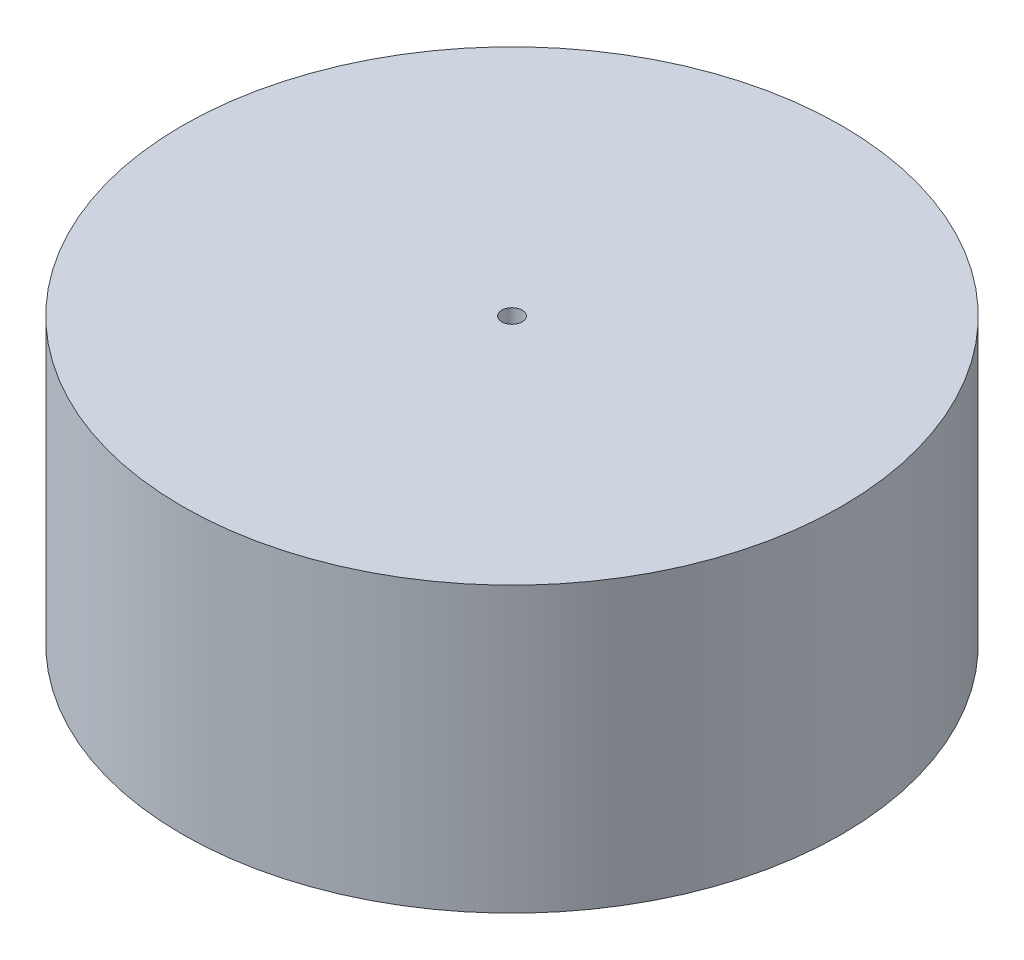
SolidWorks part; units mm, degrees
ref_plane "Front Plane" through (0, 0, 0) normal (0, 0, 1) x (1, 0, 0)
ref_plane "Top Plane" through (0, 0, 0) normal (0, 1, 0) x (1, 0, 0)
ref_plane "Right Plane" through (0, 0, 0) normal (1, 0, 0) x (0, 0, -1)
sketch "Sketch1" plane through (0, 0, 0) normal (0, 1, 0) x (1, 0, 0)
  circle A0 centre (0, 0) radius 32.5
  circle A1 centre (0, 0) radius 1
  dimension "D1" = 65
  dimension "D2" = 2
extrude "Boss-Extrude1" add sketch "Sketch1" along normal blind 3
sketch "Sketch3" plane through (0, 0, 0) normal (0, -1, 0) x (1, 0, 0)
  circle A0 centre (0, 0) radius 32.5
  circle A1 centre (0, 0) radius 30.5
  circle A2 centre (0, 0) radius 32.5 construction
  dimension "D1" = 2
extrude "Boss-Extrude2" add sketch "Sketch3" along normal blind 25
sketch "Sketch7" plane through (0, -25, 0) normal (0, -1, 0) x (1, 0, 0)
  line L0 (0, 0) -> (0, 30.5) construction
  line L1 (-42.9584, 0) -> (0, 0) construction
  line L2 (0, 0) -> (-5.2963, 30.0366)
  line L3 (0, 0) -> (5.2963, 30.0366)
  arc A0 (-5.2963, 30.0366) -> (5.2963, 30.0366) centre (0, 0) ccw
  circle A1 centre (0, 0) radius 30.5 construction
  arc A2 (-4.7753, 27.0822) -> (4.7753, 27.0822) centre (0, 0) ccw
  circle M5 centre (0, 0) radius 30.5
  dimension "D1" = 3
  dimension "D2" = 20
extrude "Boss-Extrude3" add sketch "Sketch7" against normal blind 2 contours A2 L2 L3 M5
